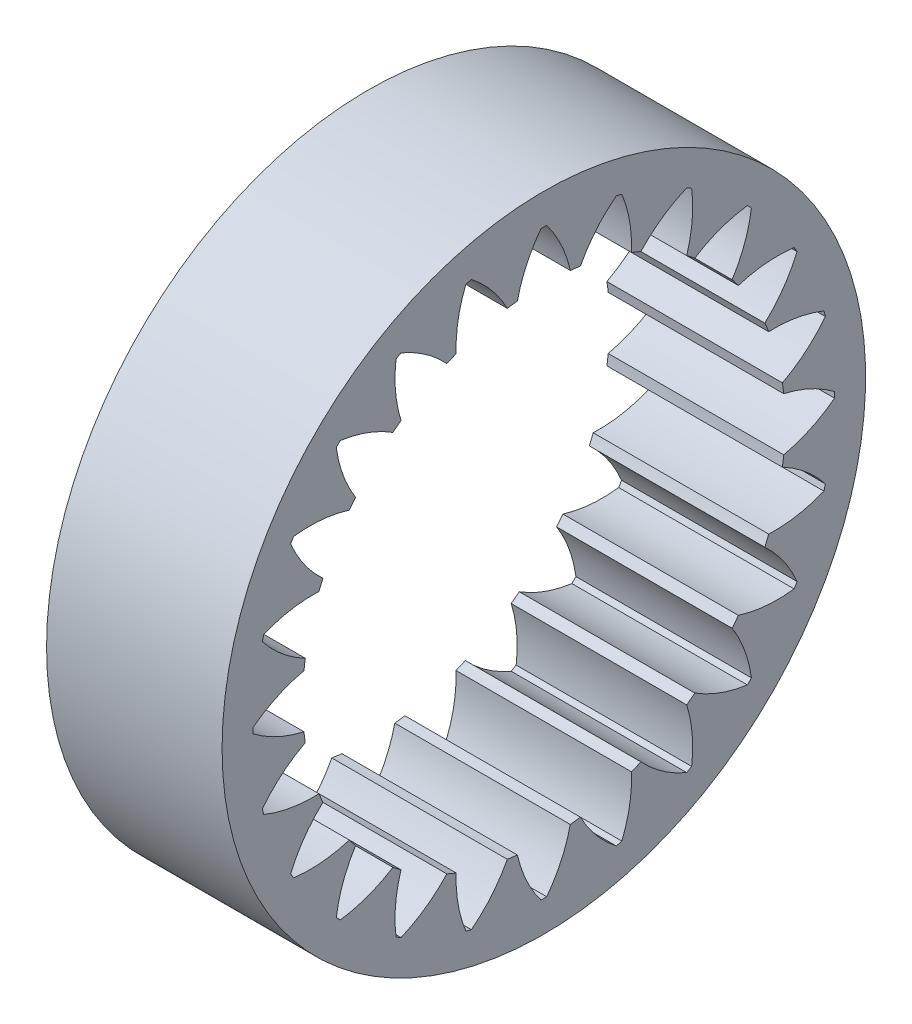
SolidWorks part; units mm, degrees
ref_plane "Plane1" through (0, 0, 0) normal (0, 0, 1) x (1, 0, 0)
ref_plane "Plane2" through (0, 0, 0) normal (0, 1, 0) x (1, 0, 0)
ref_plane "Plane3" through (0, 0, 0) normal (1, 0, 0) x (0, 0, -1)
other "Configuration Table"
sketch "HoldingSke" plane through (0, 0, 0) normal (0, 1, 0) x (1, 0, 0)
  line L0 (0, 0) -> (0.609, -0.2712)
  line L1 (-15, 0) -> (100, 0) construction
  line L2 (0, 0) -> (-2.1039, 2.3779)
  line L3 (0, 0) -> (-11.863, 4.5341)
  line L4 (0, 0) -> (7.8894, 3.5126)
  line L5 (0, 0) -> (-23.7986, -8.8762)
  line L6 (0, 0) -> (-10.5278, -7.1032)
  line L7 (-2.1039, 2.3779) -> (3.3635, 27.1825)
  line L8 (-76.2, 3.8779) -> (-54.61, 3.8779)
  line L9 (-71.009, 38.7566) -> (-53.1078, 45.2721)
  line L10 (-76.2, 71.12) -> (104.1128, 71.12)
  line L11 (0, 0) -> (-12, 0)
  line L12 (-76.2, 101.6) -> (-76.147, 101.6)
  line L13 (24.9733, 27.94) -> (52.9518, 28.4284)
  line L14 (24.9733, 27.94) -> (24.9743, 27.94)
  line L15 (24.9733, 27.94) -> (100.4006, 29.5858)
  circle A0 centre (0, 0) radius 12.5
  circle A1 centre (0, 0) radius 12.7
  circle A2 centre (0, 0) radius 12.7
  dimension "MHD" = 25.4
  dimension "Hub_dia" = 25.4
  dimension "Diameter" = 25
  dimension "Num_teeth" = 24
  dimension "Pitch" = 0.6667
  dimension "Overall_len" = 25.4
  dimension "Show_teeth" = 24
  dimension "Thickness" = 12.7
  dimension "OAL" = 25.4001
  dimension "T_dim" = 21.59
  dimension "Ap" = 20
  dimension "H" = 19.05
  dimension "Pitch_radius" = 180.3128
  dimension "Width" = 12
  dimension "Backlash" = 0.053
  dimension "Addendum_fac" = 1
  dimension "Dedendum_fac" = 1.25
  dimension "Clearance_fac" = 0.25
  dimension "Dedendum_add" = 0.001
  dimension "Module" = 1.5
sketch "BasProSke" plane through (0, 0, 0) normal (0, 1, 0) x (1, 0, 0)
  line L0 (-10, 0) -> (60, 0) construction
  line L1 (0, 16.5) -> (0, 22)
  line L2 (0, 16.5) -> (12, 16.5)
  line L3 (12, 16.5) -> (12, 22)
  line L4 (12, 22) -> (0, 22)
  dimension "Thickness" = 12
  dimension "Diameter" = 44
  dimension "Inside_diameter" = 33
revolve "Base-Revolve" add sketch "BasProSke" angle 360 about L0
sketch "TooCutSke" plane through (0, 0, 0) normal (1, 0, 0) x (0, 0, -1)
  line L3 (1.3098, 17.9523) -> (1.3098, 53.6633) construction
  line L4 (0, 0) -> (0, 59.563) construction
  line L5 (0, 0) -> (-8.9185, 67.7429) construction
  line L6 (-6.975, 14.4361) -> (35.5321, 20.0323) construction
  circle A0 centre (0, 0) radius 18 construction
  circle A1 centre (0, 0) radius 19.876 construction
  circle A2 centre (0, 0) radius 15.223 construction
  circle A3 centre (0, 0) radius 16.4746 construction
  arc A4 (1.8138, 16.3744) -> (0.1957, 19.875) centre (-6.975, 14.4361) ccw
  arc A5 (1.8138, 16.3744) -> (-1.8138, 16.3744) centre (0, 0) ccw
  arc A6 (0.1957, 19.875) -> (-0.1957, 19.875) centre (0, 0) ccw
  arc A7 (-0.1957, 19.875) -> (-1.8138, 16.3744) centre (6.975, 14.4361) ccw
  dimension "Pitch_dia" = 36
  dimension "Base_dia" = 30.446
  dimension "Root_dia" = 39.752
  dimension "Overcut_dia" = 32.9492
  dimension "Flank_rad" = 9
  dimension "Half_ang" = 7.5
  dimension "Half_CT" = 1.3098
extrude "ToothCut" cut sketch "TooCutSke" along normal through all
fillet "Breaks" [suppressed] radius 0.15
fillet "RootFillets" [suppressed] radius 0.376
pattern_circular "TeethCuts" count 24 every 15 about axis through (-10, 0, 0) along (1, 0, 0) of "RootFillets", "Breaks", "ToothCut"
equation "' \"Module@HoldingSke\" = 6.35"
equation "' \"Num_teeth@HoldingSke\" = 24"
equation "' \"Ap@HoldingSke\" =  14.5"
equation "' \"Ap@HoldingSke\" = 14.5"
equation "' \"Width@HoldingSke\" = 12"
equation "' \"Diameter@HoldingSke\" = 8 * 25.4"
equation "' \"Show_teeth@HoldingSke\" = 100"
equation "' \"Backlash@HoldingSke\" = 0.009 * 25.4"
equation "' \"Addendum_fac@HoldingSke\" = 1.0"
equation "' \"Dedendum_fac@HoldingSke\" = 1.25"
equation "' \"Dedendum_add@HoldingSke\" = 0.00005 * 25.4"
equation "' \"Clearance_fac@HoldingSke\" = 0.25"
equation "\"Pitch@HoldingSke\" = 1 / \"Module@HoldingSke\" "
equation "\"Overcut_dia@TooCutSke\" = (\"Num_teeth@HoldingSke\" - 2 * \"Addendum_fac@HoldingSke\") / \"Pitch@HoldingSke\" - 0.002 * 25.4"
equation "\"Pitch_dia@TooCutSke\" = \"Num_teeth@HoldingSke\" / \"Pitch@HoldingSke\""
equation "\"Base_dia@TooCutSke\" = \"Num_teeth@HoldingSke\" / \"Pitch@HoldingSke\" * cos((\"Ap@HoldingSke\"  * 3.14159265 / 180)) * 0.90"
equation "\"Root_dia@TooCutSke\" = \"Num_teeth@HoldingSke\"  / \"Pitch@HoldingSke\" + 2 *  \"Dedendum_fac@HoldingSke\"/ \"Pitch@HoldingSke\" + \"Dedendum_add@HoldingSke\" * 2"
equation "\"Half_ang@TooCutSke\" = 180 / \"Num_teeth@HoldingSke\""
equation "\"Half_CT@TooCutSke\" = \"Num_teeth@HoldingSke\" / \"Pitch@HoldingSke\" * sin((3.14159265 / 2 / \"Num_teeth@HoldingSke\")) / 2 + 10 * \"Backlash@HoldingSke\" / 4"
equation "\"Flank_rad@TooCutSke\" = \"Num_teeth@HoldingSke\" / \"Pitch@HoldingSke\" / 4"
equation "\"Radius@RootFillets\"= \"Clearance_fac@HoldingSke\" / \"Pitch@HoldingSke\" + \"Dedendum_add@HoldingSke\""
equation "\"Break_rad@Breaks\" = 0.02 / \"Pitch@HoldingSke\" * 5"
equation "\"Num_teeth@TeethCuts\" = int( \"Show_teeth@HoldingSke\" ) + 1"
equation "\"Num_teeth@TeethCuts\" = ((sgn( \"Num_teeth@TeethCuts\" - \"Num_teeth@HoldingSke\" )-1)*( \"Num_teeth@TeethCuts\" - \"Num_teeth@HoldingSke\" ))/-2+ \"Num_teeth@HoldingSke\""
equation "\"Num_teeth@TeethCuts\" = ((sgn( \"Num_teeth@TeethCuts\" - 2.0)+1)*( \"Num_teeth@TeethCuts\" - 2.0))/2 +2.0"
equation "\"Angle@TeethCuts\" = 360.0 / \"Num_teeth@HoldingSke\""
equation "\"Diameter@BasProSke\" = ((sgn( \"Diameter@BasProSke\"  - \"Diameter@HoldingSke\" )+1)*( \"Diameter@BasProSke\"  - \"Diameter@HoldingSke\" ))/2 + \"Diameter@HoldingSke\""
equation "\"Inside_diameter@BasProSke\" =  (\"Num_teeth@HoldingSke\" - 2 * \"Addendum_fac@HoldingSke\") / \"Pitch@HoldingSke\" "
equation "\"Thickness@BasProSke\"  = \"Width@HoldingSke\""
